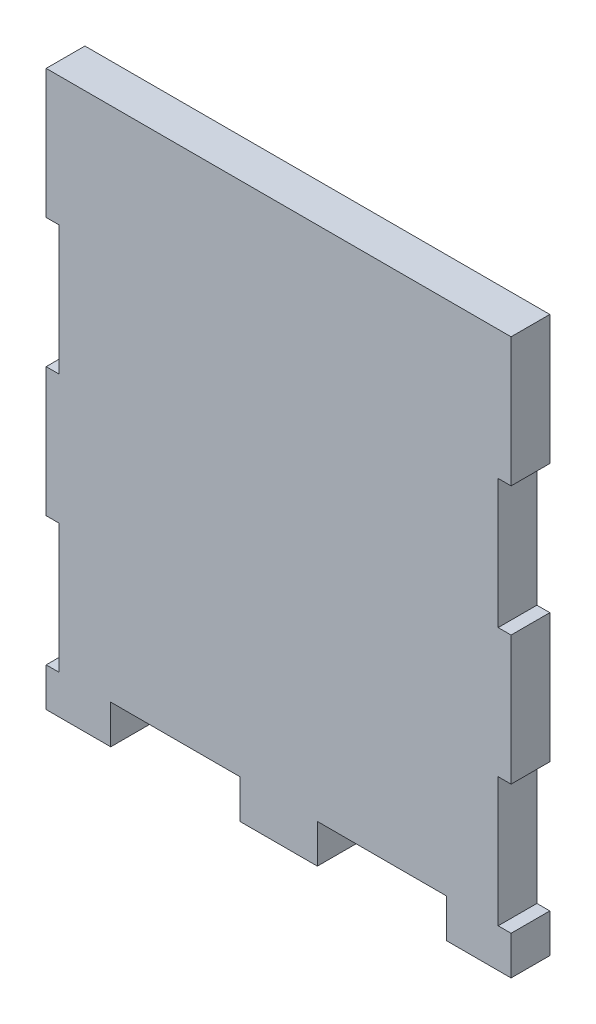
SolidWorks part; units mm, degrees
material "Acrylic (Medium-high impact)"
ref_plane "Front Plane" through (0, 0, 0) normal (0, 0, 1) x (1, 0, 0)
ref_plane "Top Plane" through (0, 0, 0) normal (0, 1, 0) x (1, 0, 0)
ref_plane "Right Plane" through (0, 0, 0) normal (1, 0, 0) x (0, 0, -1)
sketch "Sketch1" plane through (0, 0, 0) normal (0, 0, 1) x (1, 0, 0)
  line L0 (0, 0) -> (0, 40)
  line L1 (0, 40) -> (36, 40)
  line L2 (36, 40) -> (36, 0)
  line L3 (36, 0) -> (0, 0)
  line L4 (18, 0) -> (18, 40) construction
  line L5 (36, 10) -> (35, 10)
  line L6 (0, 0) -> (1, 0)
  line L7 (0, 0) -> (0, 10)
  line L8 (0, 10) -> (1, 10)
  line L9 (1, 0) -> (1, 10)
  line L10 (0, 20) -> (1, 20)
  line L11 (0, 20) -> (0, 30)
  line L12 (0, 30) -> (1, 30)
  line L13 (1, 20) -> (1, 30)
  line L14 (35, 0) -> (35, 10)
  line L15 (36, 0) -> (35, 0)
  line L16 (36, 0) -> (36, 10)
  line L17 (36, 30) -> (35, 30)
  line L18 (35, 20) -> (35, 30)
  line L19 (36, 20) -> (35, 20)
  line L20 (36, 20) -> (36, 30)
  line L21 (1, 20) -> (1, 10)
  line L22 (35, 20) -> (35, 10)
  line L23 (35, 30) -> (35, 40)
  line L24 (1, 30) -> (1, 40)
  line L25 (0, 0) -> (0, -3)
  line L26 (5, 0) -> (15, 0)
  line L27 (5, 0) -> (5, -3)
  line L28 (5, -3) -> (15, -3)
  line L29 (15, 0) -> (15, -3)
  line L30 (21, 0) -> (31, 0)
  line L31 (21, 0) -> (21, -3)
  line L32 (21, -3) -> (31, -3)
  line L33 (31, 0) -> (31, -3)
  line L34 (0, -3) -> (36, -3)
  line L35 (36, -3) -> (36, 0)
  dimension "D1" = 40
  dimension "D2" = 36
  dimension "D3" = 10
  dimension "D4" = 10
  dimension "D5" = 1
  dimension "D6" = 10
  dimension "D7" = 5
  dimension "D8" = 5
  dimension "D9" = 3
extrude "Boss-Extrude1" add sketch "Sketch1" along normal blind 3 contours L3 L4 L1 L24 L13 L21 L9 | L4 L3 L14 L22 L18 L23 L1 | L23 L17 L2 L1 | L12 L24 L1 L0 | L21 L10 L0 L8 | L19 L22 L5 L2 | L25 L34 L27 L3 | L29 L34 L31 L3 | L34 L35 L3 L33
